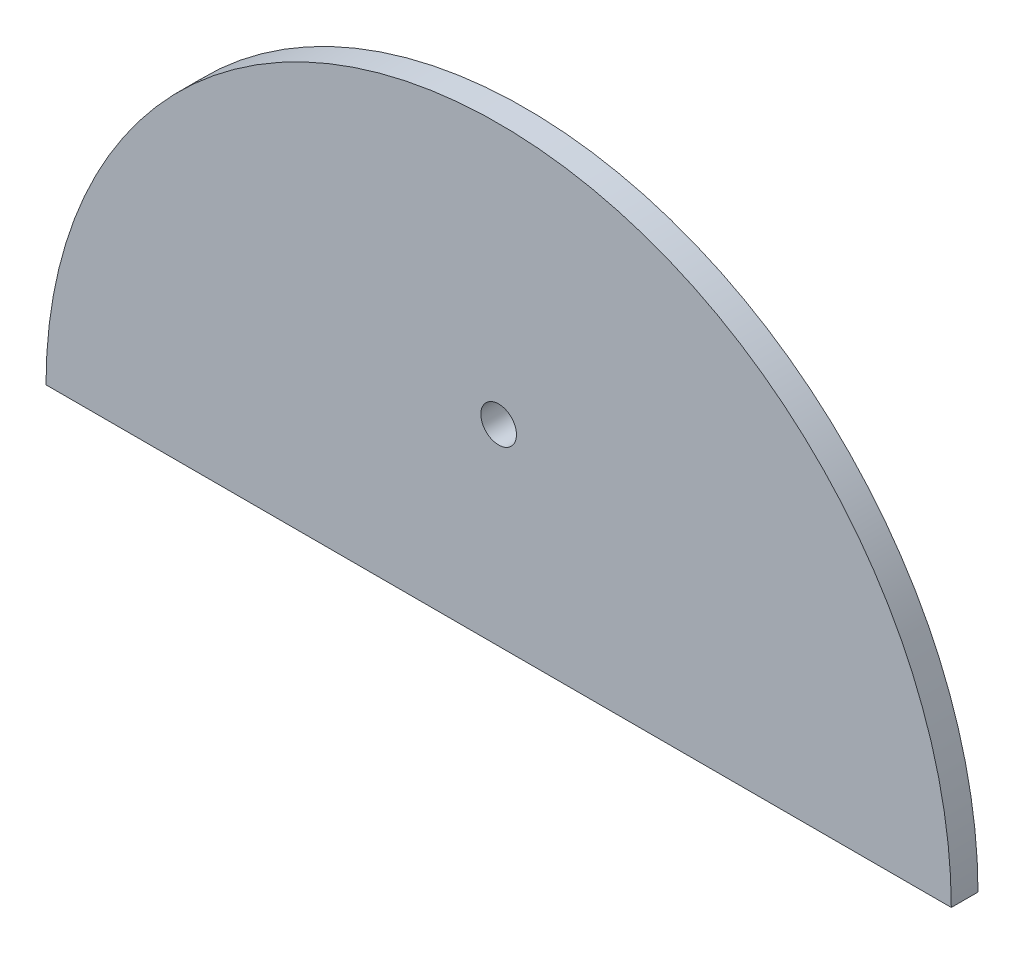
SolidWorks part; units mm, degrees
ref_plane "Front Plane" through (0, 0, 0) normal (0, 0, 1) x (1, 0, 0)
ref_plane "Top Plane" through (0, 0, 0) normal (0, 1, 0) x (1, 0, 0)
ref_plane "Right Plane" through (0, 0, 0) normal (1, 0, 0) x (0, 0, -1)
sketch "Sketch1" plane through (0, 0, 0) normal (0, 0, 1) x (1, 0, 0)
  line L0 (-50.85, 0) -> (50.85, 0)
  arc A0 (-50.85, 0) -> (50.85, 0) centre (0, 0) cw
  dimension "D1" = 101.7
extrude "Boss-Extrude1" add sketch "Sketch1" along normal blind 3
sketch "Sketch2" plane through (0, 0, 3) normal (0, 0, 1) x (1, 0, 0)
  line L0 (-50.85, 0) -> (50.85, 0) construction
  circle A0 centre (0, 21.5727) radius 2
  dimension "D1" = 4
  dimension "D2" = 21.5727
extrude "Cut-Extrude1" cut sketch "Sketch2" against normal through all
